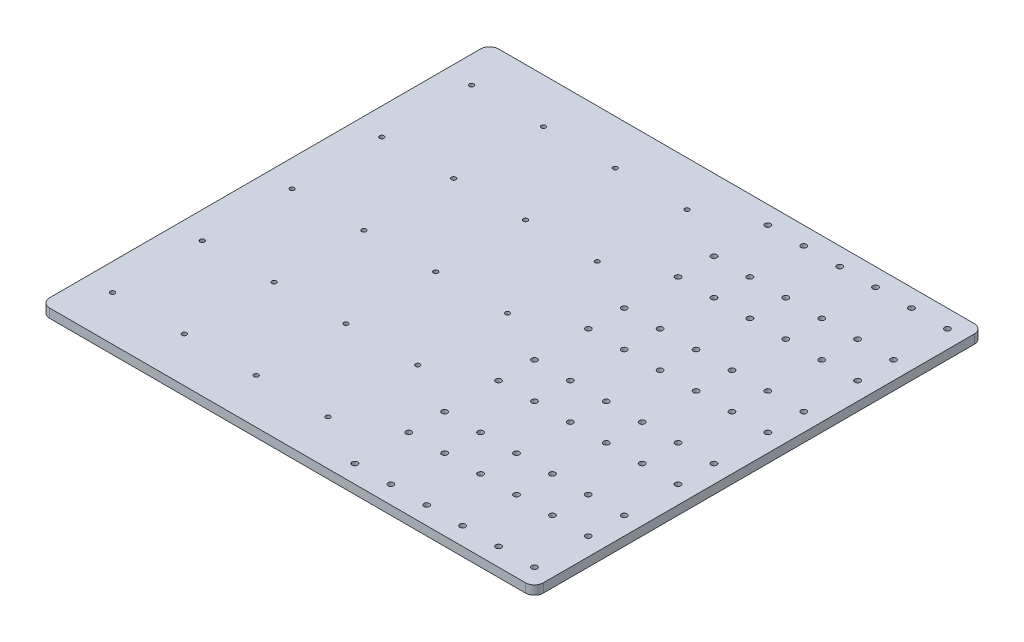
SolidWorks part; units mm, degrees
ref_plane "Front Plane" through (0, 0, 0) normal (0, 0, 1) x (1, 0, 0)
ref_plane "Top Plane" through (0, 0, 0) normal (0, 1, 0) x (1, 0, 0)
ref_plane "Right Plane" through (0, 0, 0) normal (1, 0, 0) x (0, 0, -1)
sketch "Sketch2" plane through (0, 0, 0) normal (0, 1, 0) x (1, 0, 0)
  line L1 (-137.5, 25) -> (137.5, 25)
  line L2 (-137.5, 25) -> (-137.5, -25)
  line L3 (-137.5, -25) -> (137.5, -25)
  line L4 (137.5, 25) -> (137.5, -25)
  line L5 (-137.5, 25) -> (137.5, -25) construction
  line L6 (-137.5, -25) -> (137.5, 25) construction
  point P0 (0, 0)
  dimension "D1" = 50
  dimension "D2" = 275
extrude "Boss-Extrude1" add sketch "Sketch2" along normal blind 5
sketch "Sketch3" plane through (0, 0, 0) normal (0, -1, 0) x (1, 0, 0)
  line L0 (-1000, 0) -> (49000, 0) construction
  line L1 (-137.5, -25) -> (-137.5, 25) construction
  circle A0 centre (-122.5, 0) radius 1.25
  circle A1 centre (-82.5, 0) radius 1.25
  circle A2 centre (-42.5, 0) radius 1.25
  circle A3 centre (-2.5, 0) radius 1.25
  dimension "D1" = 15
  dimension "D2" = 2.5
  dimension "D3" = 2.5
  dimension "D4" = 2.5
  dimension "D5" = 40
  dimension "D6" = 40
  dimension "D7" = 40
  dimension "D8" = 2.5
extrude "Cut-Extrude1" cut sketch "Sketch3" against normal through all
sketch "Sketch5" plane through (0, 0, 0) normal (0, -1, 0) x (1, 0, 0)
  line L0 (-1000, 0) -> (49000, 0) construction
  line L1 (127.5, -1000) -> (127.5, 49000) construction
  line L2 (137.5, 25) -> (137.5, -25) construction
  circle A0 centre (127.5, 15) radius 1.55
  circle A1 centre (127.5, -15) radius 1.55
  dimension "D2" = 3.1
  dimension "D3" = 3.1
  dimension "D5" = 15
  dimension "D1" = 10
  dimension "D4" = 15
extrude "Cut-Extrude3" cut sketch "Sketch5" against normal through all
pattern_linear "LPattern1" count 6 spacing 20 along (-1, 0, 0) of "Cut-Extrude3"
pattern_linear "LPattern3" count 5 spacing 50 along (0, 0, -1) of "Boss-Extrude1", "Cut-Extrude1", "Cut-Extrude3", "LPattern1"
fillet "Fillet1" radius 5 4 edges at (-137.5, 2.5, 25) (137.5, 2.5, 25) (-137.5, 2.5, -225) (137.5, 2.5, -225)
